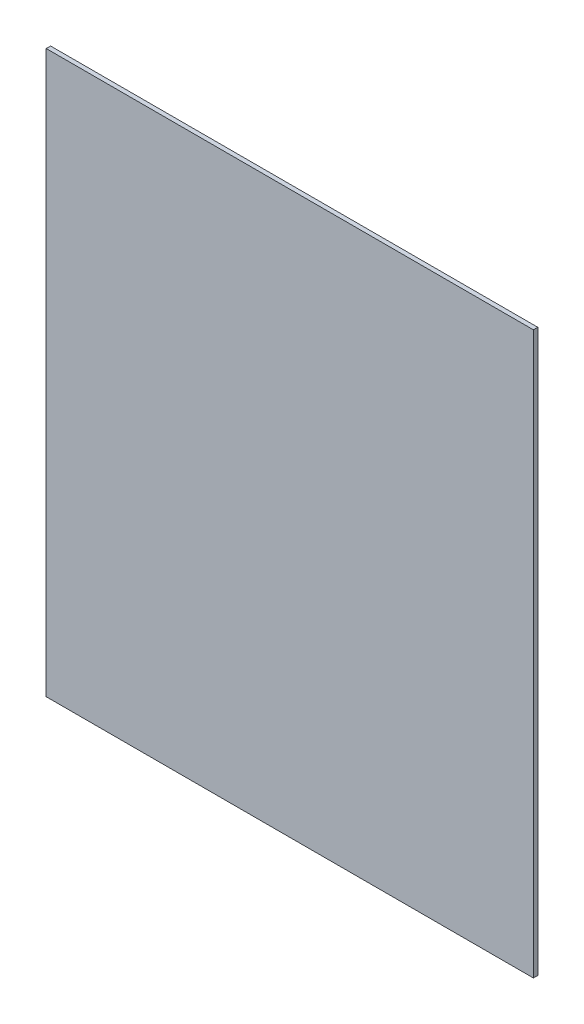
SolidWorks part; units mm, degrees
ref_plane "Plan de face" through (0, 0, 0) normal (0, 0, 1) x (1, 0, 0)
ref_plane "Plan de dessus" through (0, 0, 0) normal (0, 1, 0) x (1, 0, 0)
ref_plane "Plan de droite" through (0, 0, 0) normal (1, 0, 0) x (0, 0, -1)
sketch "Esquisse1" plane through (0, 0, 0) normal (0, 0, 1) x (1, 0, 0)
  line L1 (-361, -416) -> (361, -416)
  line L2 (-361, -416) -> (-361, 416)
  line L3 (-361, 416) -> (361, 416)
  line L4 (361, -416) -> (361, 416)
  line L5 (-361, -416) -> (361, 416) construction
  line L6 (-361, 416) -> (361, -416) construction
  point P0 (0, 0)
  dimension "D1" = 832
  dimension "D2" = 722
extrude "Boss.-Extru.1" add sketch "Esquisse1" along normal blind 6.5
